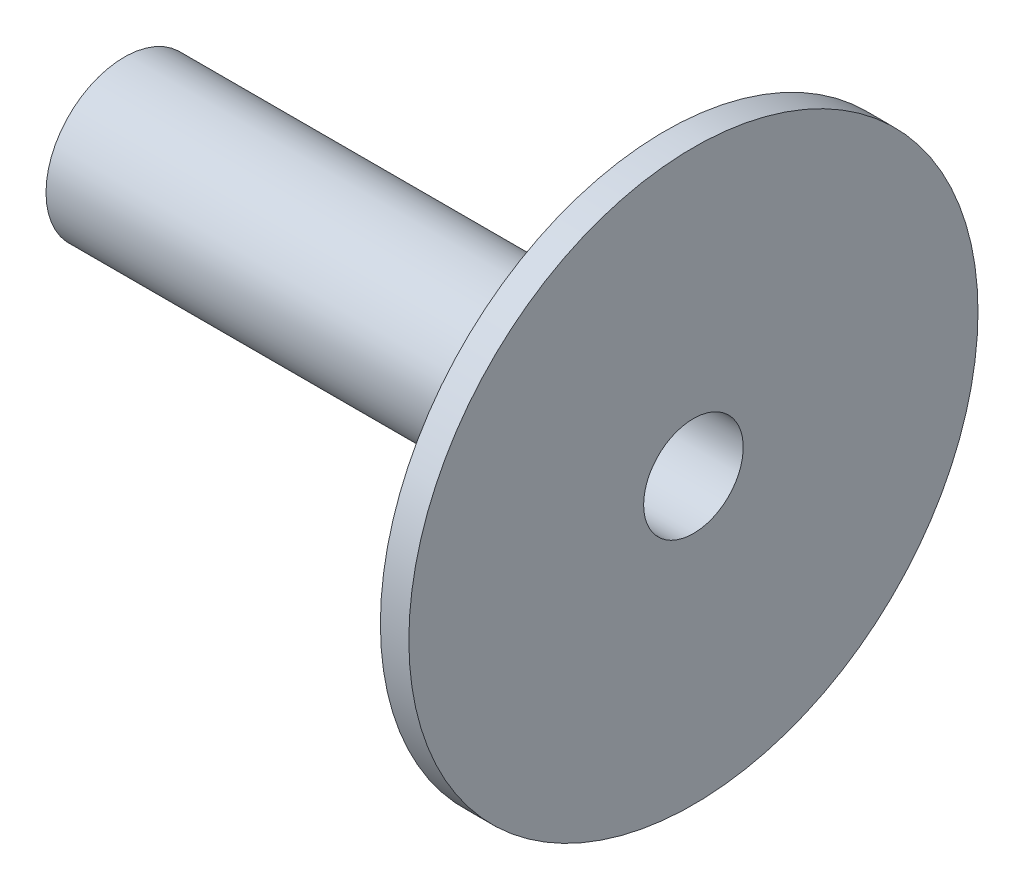
SolidWorks part; units mm, degrees
ref_plane "Front Plane" through (0, 0, 0) normal (0, 0, 1) x (1, 0, 0)
ref_plane "Top Plane" through (0, 0, 0) normal (0, 1, 0) x (1, 0, 0)
ref_plane "Right Plane" through (0, 0, 0) normal (1, 0, 0) x (0, 0, -1)
sketch "Sketch1" plane through (0, 0, 0) normal (1, 0, 0) x (0, 0, -1)
  circle A0 centre (0, 0) radius 20
  dimension "D1" = 40
extrude "Boss-Extrude1" add sketch "Sketch1" along normal blind 40
sketch "Sketch2" plane through (0, 0, 0) normal (-1, 0, 0) x (0, 0, 1)
  circle A0 centre (0, 0) radius 20
  circle A1 centre (0, 0) radius 5.5
  dimension "D1" = 11
extrude "Cut-Extrude1" cut sketch "Sketch2" against normal blind 38
sketch "Sketch3" plane through (0, 0, 0) normal (-1, 0, 0) x (0, 0, 1)
  circle A0 centre (0, 0) radius 3.5
  dimension "D1" = 7
extrude "Cut-Extrude2" cut sketch "Sketch3" against normal blind 40
